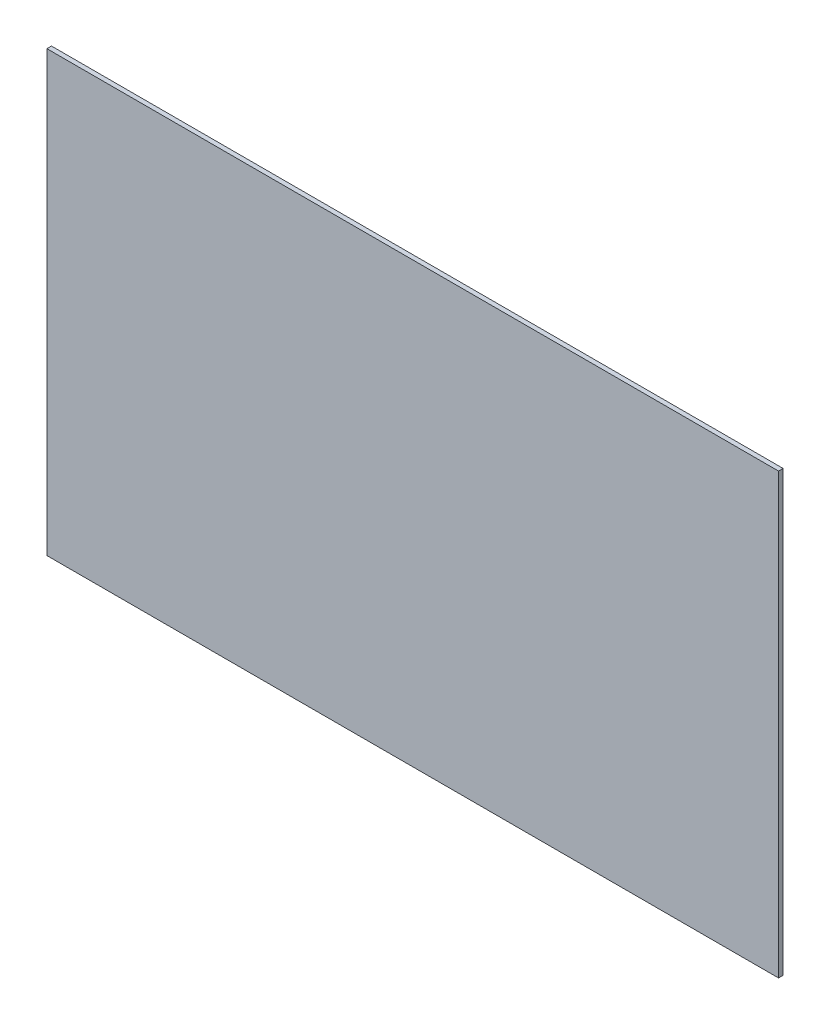
SolidWorks part; units mm, degrees
ref_plane "Front Plane" through (0, 0, 0) normal (0, 0, 1) x (1, 0, 0)
ref_plane "Top Plane" through (0, 0, 0) normal (0, 1, 0) x (1, 0, 0)
ref_plane "Right Plane" through (0, 0, 0) normal (1, 0, 0) x (0, 0, -1)
sketch "Sketch1" plane through (0, 0, 0) normal (0, 0, 1) x (1, 0, 0)
  line L1 (-254, -152.4) -> (254, -152.4)
  line L2 (-254, -152.4) -> (-254, 152.4)
  line L3 (-254, 152.4) -> (254, 152.4)
  line L4 (254, -152.4) -> (254, 152.4)
  line L5 (-254, -152.4) -> (254, 152.4) construction
  line L6 (-254, 152.4) -> (254, -152.4) construction
  point P0 (0, 0)
  dimension "D1" = 508
  dimension "D2" = 304.8
extrude "Boss-Extrude1" add sketch "Sketch1" along normal mid plane 3.175
